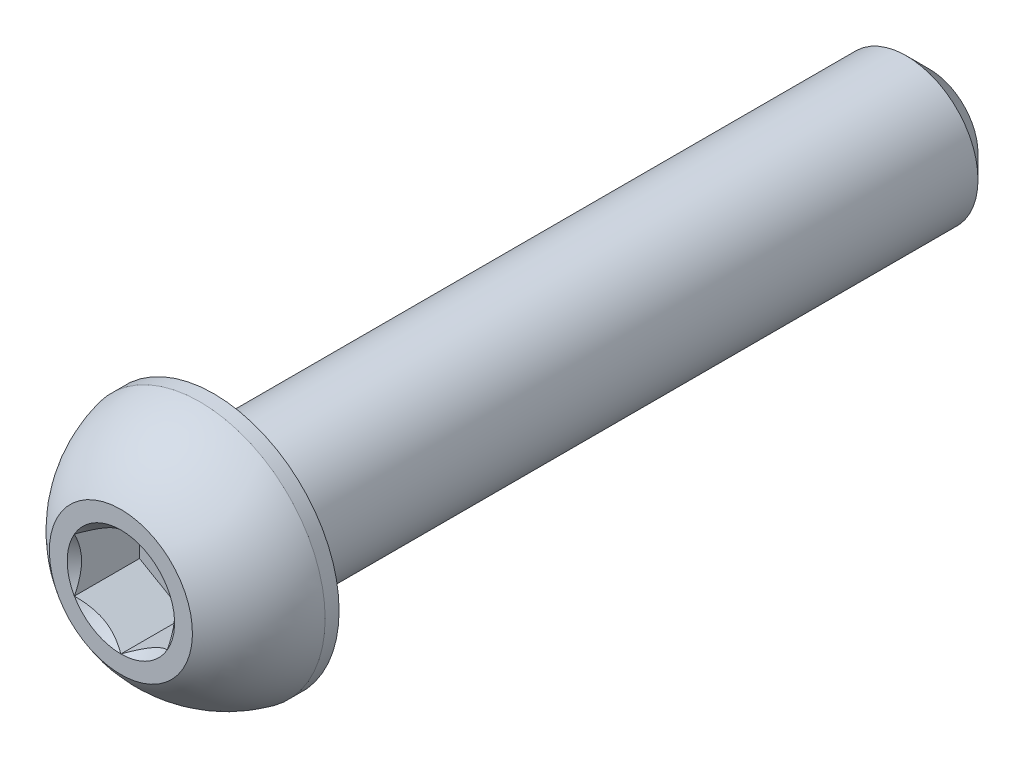
SolidWorks part; units mm, degrees
ref_plane "Front Plane" through (0, 0, 0) normal (0, 0, 1) x (1, 0, 0)
ref_plane "Top Plane" through (0, 0, 0) normal (0, 1, 0) x (1, 0, 0)
ref_plane "Right Plane" through (0, 0, 0) normal (1, 0, 0) x (0, 0, -1)
sketch "Sketch1" plane through (0, 0, 0) normal (1, 0, 0) x (0, 0, -1)
  line L0 (-5.65, 0) -> (5.65, 0) construction
  line L1 (-4.35, 1.75) -> (-4.35, -1.75) construction
  line L2 (5.65, 1) -> (5.65, -1) construction
  line L3 (5.625, 1.0433) -> (5.825, 0.6969) construction
  line L4 (5.825, 0.6969) -> (6.025, 1.0433) construction
  line L5 (6.025, 1.0433) -> (5.625, 1.0433) construction
  line L6 (5.65, 1) -> (6, 1) construction
  line L7 (5.825, 1.0433) -> (5.825, 1) construction
  line L8 (5.825, 1) -> (5.825, 0.7402) construction
  line L9 (5.825, 0.7402) -> (5.825, 0.6969) construction
  line L10 (5.8, 0.7402) -> (5.85, 0.7402)
  line L11 (5.6375, 1.0217) -> (6.0125, 1.0217)
  line L12 (5.85, 0.7402) -> (6.0125, 1.0217)
  line L13 (5.8, 0.7402) -> (5.6375, 1.0217)
  line L14 (-5.65, 0.65) -> (-5.65, -0.65) construction
  line L15 (5.65, 1) -> (-4.35, 1) construction
  point P3 (-4.35, 0)
  point P6 (-4.74, 0)
  point P21 (5.825, 1.0217)
  point P24 (-4.545, 1.75)
  point P25 (4.65, -1)
  point P26 (-5.65, 1)
  dimension "Head Height" = 1.3
  dimension "Length" = 10
  dimension "Head Dia" = 3.5
  dimension "Thread Dia" = 2
  dimension "Pitch" = 0.4
  dimension "D2" = 0.05
  dimension "Drive Size" = 1.3
  dimension "D1" = 0.91
  dimension "D3" = 0.195
  dimension "D4" = 1
sketch "Sketch2" plane through (0, 0, 0) normal (1, 0, 0) x (0, 0, -1)
  line L0 (-5.65, 0) -> (5.65, 0)
  line L1 (5.65, 0) -> (5.65, 0.68)
  line L2 (5.65, 1) -> (5.65, -1) construction
  line L3 (5.65, 0.68) -> (5.33, 1)
  line L4 (5.33, 1) -> (-4.35, 1)
  line L5 (-4.35, 1.75) -> (-4.35, -1.75) construction
  line L6 (-4.35, 1) -> (-4.35, 1.75)
  line L7 (-4.35, 1.75) -> (-4.545, 1.75)
  line L8 (5.65, 1) -> (6, 1) construction
  line L9 (-5.65, 0) -> (-5.65, 1)
  arc A0 (-5.65, 1) -> (-4.545, 1.75) centre (-4.1642, 0) cw
  dimension "D1" = 0.32
  dimension "D2" = 45
revolve "Revolve1" add sketch "Sketch2" angle 360 about L0
sketch "Sketch3" plane through (0, 0, 5.65) normal (0, 0, 1) x (1, 0, 0)
  line L1 (0, 0.7506) -> (-0.65, 0.3753)
  line L2 (-0.65, 0.3753) -> (-0.65, -0.3753)
  line L3 (-0.65, -0.3753) -> (0, -0.7506)
  line L4 (0, -0.7506) -> (0.65, -0.3753)
  line L5 (0.65, -0.3753) -> (0.65, 0.3753)
  line L6 (0.65, 0.3753) -> (0, 0.7506)
  circle A0 centre (0, 0) radius 0.65 construction
  dimension "D1" = 1.3
extrude "Cut-Extrude1" cut sketch "Sketch3" against normal up to vertex (0.91 mm away) up to point (0, 0, 4.74)
sketch "Sketch4" plane through (0, 0, 5.65) normal (0, 0, 1) x (1, 0, 0)
  circle A0 centre (0, 0) radius 0.7506
extrude "Cut-Extrude2" cut sketch "Sketch4" against normal blind 10 draft 45
sketch "Sketch6" plane through (0, 0, 0) normal (1, 0, 0) x (0, 0, -1)
  line L0 (5.8, 0.7402) -> (5.85, 0.7402) construction
  line L1 (5.8, 0.7402) -> (5.6375, 1.0217) construction
  line L2 (5.6375, 1.0217) -> (6.0125, 1.0217) construction
  line L3 (5.85, 0.7402) -> (6.0125, 1.0217) construction
  line L4 (5.8, 0.7402) -> (5.85, 0.7402)
  line L5 (5.8, 0.7402) -> (5.6375, 1.0217)
  line L6 (5.6375, 1.0217) -> (6.0125, 1.0217)
  line L7 (5.85, 0.7402) -> (6.0125, 1.0217)
equation "\"D2@Sketch1\" = \"Pitch@Sketch1\" / 8"
equation "\"D1@Sketch1\"=\"Drive Size@Sketch1\"*.7"
equation "\"D3@Sketch1\"=\"Head Height@Sketch1\"*.15"
equation "\"D1@Sketch2\"=\"Pitch@Sketch1\"*.8"
equation "\"D1@Sketch3\"=\"Drive Size@Sketch1\""
equation "\"D4@Sketch1\"=\"Pitch@Sketch1\"*2.5"
